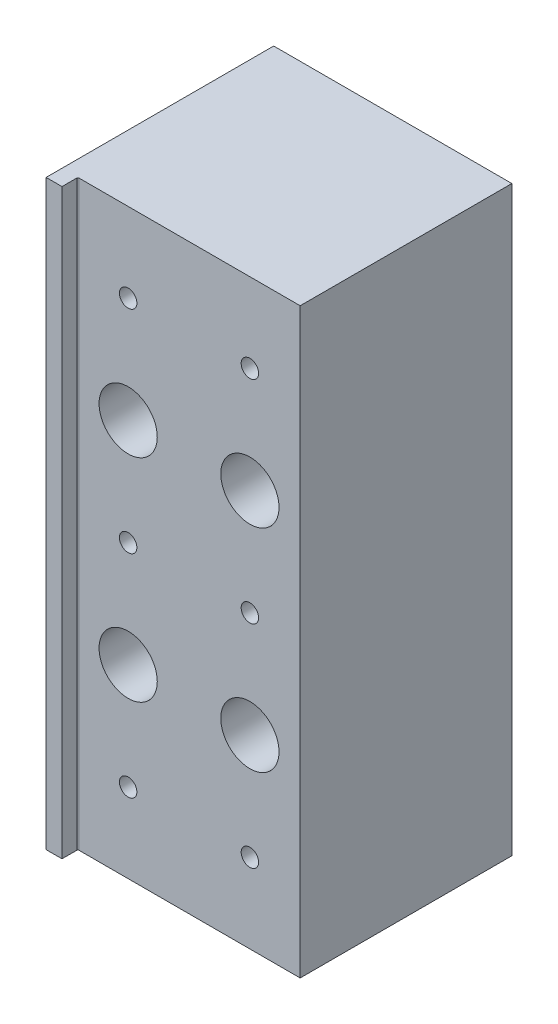
SolidWorks part; units mm, degrees
ref_plane "정면" through (0, 0, 0) normal (0, 0, 1) x (1, 0, 0)
ref_plane "윗면" through (0, 0, 0) normal (0, 1, 0) x (1, 0, 0)
ref_plane "우측면" through (0, 0, 0) normal (1, 0, 0) x (0, 0, -1)
sketch "스케치1" plane through (0, 0, 0) normal (0, 1, 0) x (1, 0, 0)
  line L0 (0, -43) -> (0, 0)
  line L1 (3, -40) -> (45, -40)
  line L3 (0, 0) -> (45, 0)
  line L4 (45, -40) -> (45, 0)
  line L7 (0, -43) -> (3, -43)
  line L8 (3, -40) -> (3, -43)
  dimension "D1" = 3
  dimension "D2" = 42
  dimension "D3" = 40
  dimension "D4" = 3
extrude "보스-돌출1" add sketch "스케치1" along normal blind 110
fillet "필렛1" radius 0.2 1 edges at (3, 55, 40)
sketch "스케치2" plane through (0, 0, 40) normal (0, 0, 1) x (1, 0, 0)
  line L0 (0, 110) -> (0, 0) construction
  circle A0 centre (12.5, 75) radius 5.5
  circle A1 centre (35.5, 75) radius 5.5
  circle A2 centre (12.5, 35) radius 5.5
  circle A3 centre (35.5, 35) radius 5.5
  dimension "D1" = 11
  dimension "D2" = 35
  dimension "D3" = 40
  dimension "D4" = 12.5
  dimension "D5" = 23
extrude "컷-돌출1" cut sketch "스케치2" against normal blind 8
sketch "스케치3" plane through (0, 0, 32) normal (0, 0, 1) x (1, 0, 0)
  circle A0 centre (12.5, 75) radius 3.5
  circle A1 centre (35.5, 75) radius 3.5
  circle A2 centre (35.5, 35) radius 3.5
  circle A3 centre (12.5, 35) radius 3.5
  dimension "D1" = 7
extrude "컷-돌출2" cut sketch "스케치3" against normal through all
sketch "스케치4" plane through (0, 0, 40) normal (0, 0, 1) x (1, 0, 0)
  line L0 (3.2, 0) -> (45, 0) construction
  line L1 (0, 110) -> (0, 0) construction
  point P0 (12.5, 95)
  point P1 (12.5, 15)
  point P2 (12.5, 55)
  point P3 (35.5, 55)
  point P4 (35.5, 95)
  point P5 (35.5, 15)
  dimension "D1" = 15
  dimension "D2" = 40
  dimension "D3" = 40
  dimension "D4" = 12.5
  dimension "D5" = 23
hole_wizard "M4 나사 구멍1" positions "스케치4" profile "스케치5" tap size "M4" standard "ISO"
sketch "스케치5" plane through (12.5, 95, 40) normal (1, 0, 0) x (0, -1, 0)
  line L0 (0, 0) -> (0, 17.4914)
  line L1 (0, 17.4914) -> (1.65, 16.5)
  line L2 (1.65, 16.5) -> (1.65, 0)
  line L5 (1.65, 0) -> (0, 0)
  line L10 (0, 17.4914) -> (-1.65, 16.5) construction
  line L11 (0, -6.35) -> (0, 107.95) construction
  dimension "탭 드릴 지름" = 3.3
  dimension "탭 드릴 깊이" = 16.5
  dimension "드릴 각도" = 118
cosmetic thread "구멍 나사산1" parameters "D1"=13, "D2"=4
cosmetic thread "구멍 나사산2" parameters "D1"=13, "D2"=4
cosmetic thread "구멍 나사산3" parameters "D1"=13, "D2"=4
cosmetic thread "구멍 나사산4" parameters "D1"=13, "D2"=4
cosmetic thread "구멍 나사산5" parameters "D1"=13, "D2"=4
cosmetic thread "구멍 나사산6" parameters "D1"=13, "D2"=4
ref_plane "평면1" through (22.5, 0, 0) normal (1, 0, 0) x (0, 0, -1)
